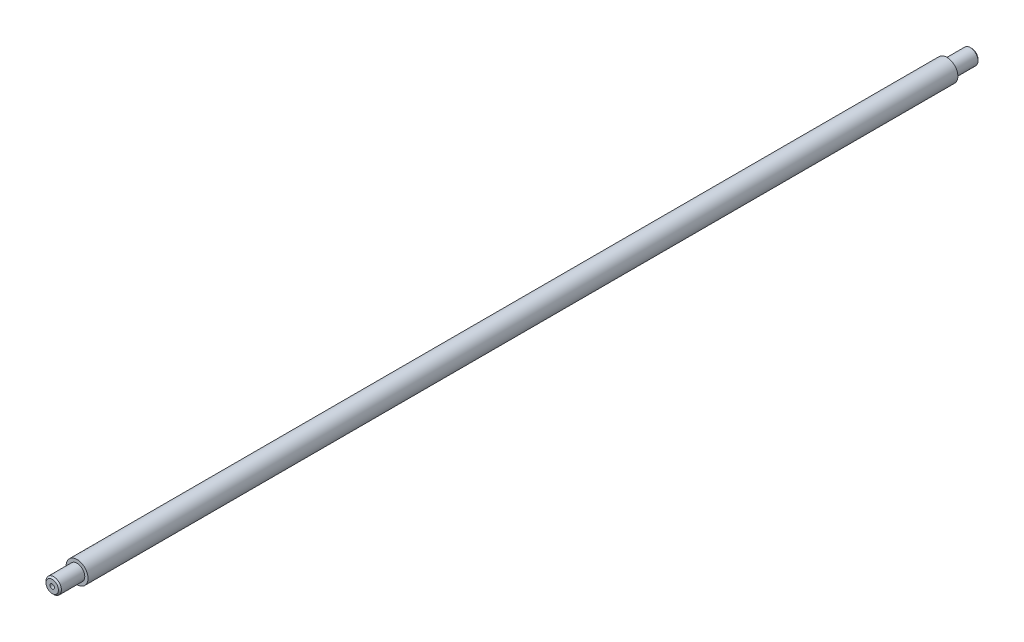
SolidWorks part; units mm, degrees
material "Balsa"
ref_plane "Front Plane" through (0, 0, 0) normal (0, 0, 1) x (1, 0, 0)
ref_plane "Top Plane" through (0, 0, 0) normal (0, 1, 0) x (1, 0, 0)
ref_plane "Right Plane" through (0, 0, 0) normal (1, 0, 0) x (0, 0, -1)
sketch "Sketch2" plane through (0, 0, 0) normal (0, 0, 1) x (1, 0, 0)
  circle A0 centre (0, 0) radius 5.588
  dimension "D1" = 11.176
extrude "Boss-Extrude1" add sketch "Sketch2" along normal mid plane 444.5
sketch "Sketch3" plane through (0, 0, 222.25) normal (0, 0, 1) x (1, 0, 0)
  circle A0 centre (0, 0) radius 3.937
  circle A1 centre (0, 0) radius 5.588
  circle A2 centre (0, 0) radius 5.588
  dimension "D2" = 7.874
  dimension "D1" = 0
extrude "Boss-Extrude2" add sketch "Sketch3" along normal blind 12.7 contours A0
sketch "Sketch4" plane through (0, 0, -222.25) normal (0, 0, -1) x (-1, 0, 0)
  circle A0 centre (0, 0) radius 3.937
  circle A1 centre (0, 0) radius 5.588
  circle A2 centre (0, 0) radius 5.588
  dimension "D2" = 7.874
  dimension "D1" = 0
extrude "Boss-Extrude3" add sketch "Sketch4" along normal blind 12.7 contours A0
sketch "Sketch5" plane through (0, 0, 234.95) normal (0, 0, 1) x (1, 0, 0)
  circle A0 centre (0, 0) radius 1.143
  circle A1 centre (0, 0) radius 3.937
  circle A2 centre (0, 0) radius 3.937
  dimension "D2" = 2.286
  dimension "D1" = 0
extrude "Cut-Extrude1" cut sketch "Sketch5" against normal blind 25.4 contours A0
sketch "Sketch6" plane through (0, 0, -234.95) normal (0, 0, -1) x (-1, 0, 0)
  circle A0 centre (0, 0) radius 1.143
  circle A1 centre (0, 0) radius 3.937
  circle A2 centre (0, 0) radius 3.937
  dimension "D2" = 2.286
  dimension "D1" = 0
extrude "Cut-Extrude2" cut sketch "Sketch6" against normal blind 25.4 contours A0
chamfer "Chamfer2" distance 0.762 angle 45 2 edges at (-3.937, 0, -234.95) (3.937, 0, 234.95)
